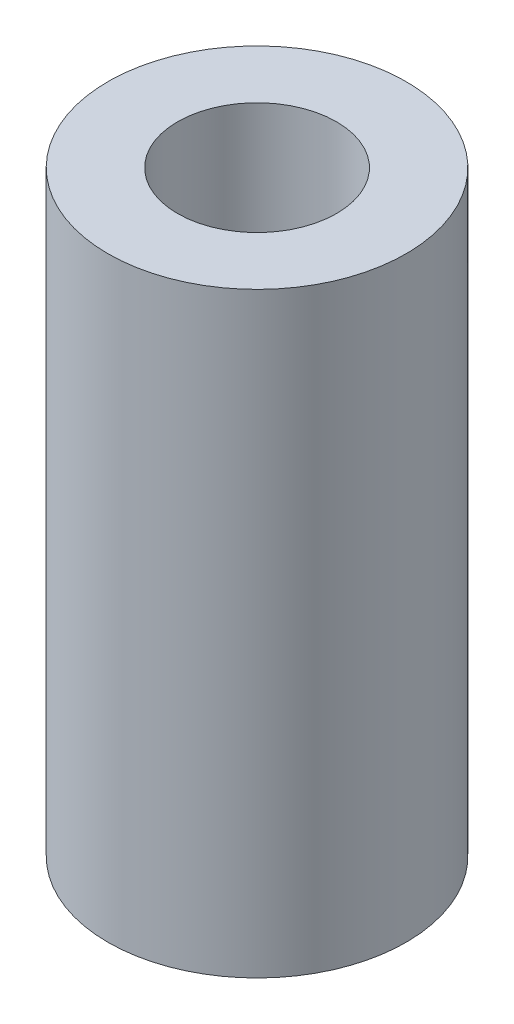
SolidWorks part; units mm, degrees
material "Alloy Steel"
ref_plane "Front" through (0, 0, 0) normal (0, 0, 1) x (1, 0, 0)
ref_plane "Top" through (0, 0, 0) normal (0, 1, 0) x (1, 0, 0)
ref_plane "Right" through (0, 0, 0) normal (1, 0, 0) x (0, 0, -1)
sketch "Sketch1" plane through (0, 0, 0) normal (0, 1, 0) x (1, 0, 0)
  circle A0 centre (0, 0) radius 8
  circle A1 centre (0, 0) radius 15
  dimension "D1" = 30
  dimension "D2" = 16
extrude "Boss-Extrude1" add sketch "Sketch1" along normal mid plane 60
